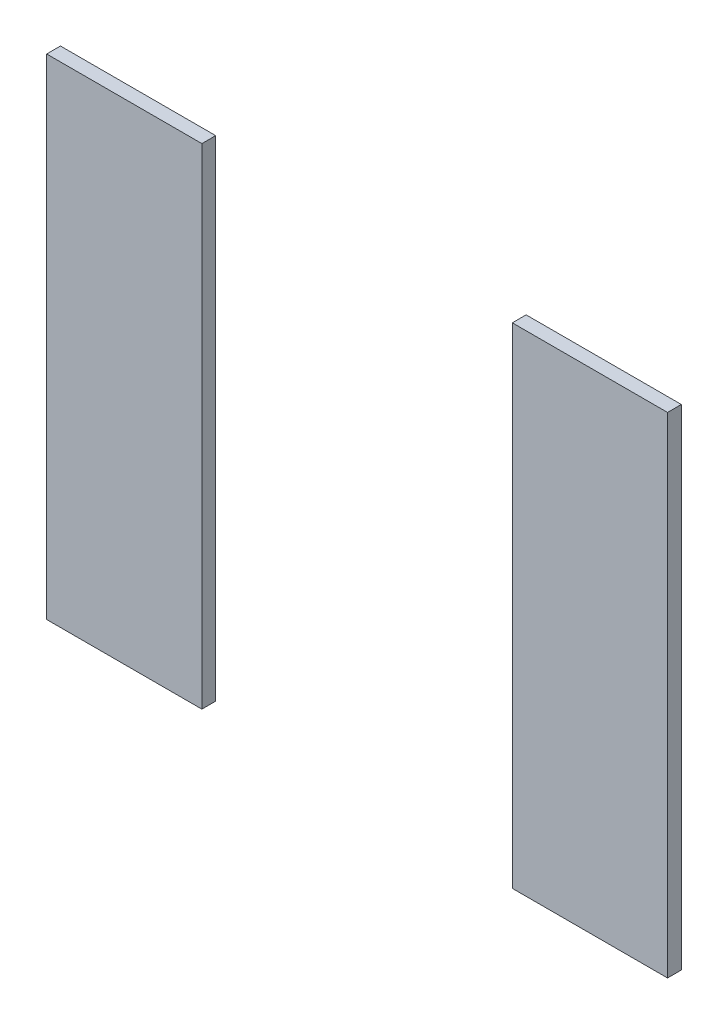
SolidWorks part; units mm, degrees
ref_plane "Front Plane" through (0, 0, 0) normal (0, 0, 1) x (1, 0, 0)
ref_plane "Top Plane" through (0, 0, 0) normal (0, 1, 0) x (1, 0, 0)
ref_plane "Right Plane" through (0, 0, 0) normal (1, 0, 0) x (0, 0, -1)
sketch "Sketch2" plane through (0, 0, 0) normal (0, 0, 1) x (1, 0, 0)
  line L0 (-450, 0) -> (450, 0)
  line L1 (-450, 0) -> (-450, -810)
  line L2 (450, 0) -> (450, -810)
  line L3 (-450, -810) -> (450, -810)
  line L4 (-225, 0) -> (-225, -810)
  line L5 (225, -810) -> (225, 0)
  line L6 (450, -243.561) -> (225, -243.561) construction
  line L7 (-450, -243.561) -> (-225, -243.561) construction
  line L8 (-450, -710) -> (450, -710)
  line L9 (390.1466, -710) -> (390.1466, -810) construction
  point P2 (0, 0)
  dimension "D1" = 225
  dimension "D2" = 810
  dimension "D3" = 900
  dimension "D4" = 100
extrude "Boss-Extrude1" add sketch "Sketch2" along normal mid plane 20 contours L4 L0 L1 L3 | L5 L3 L2 L0
